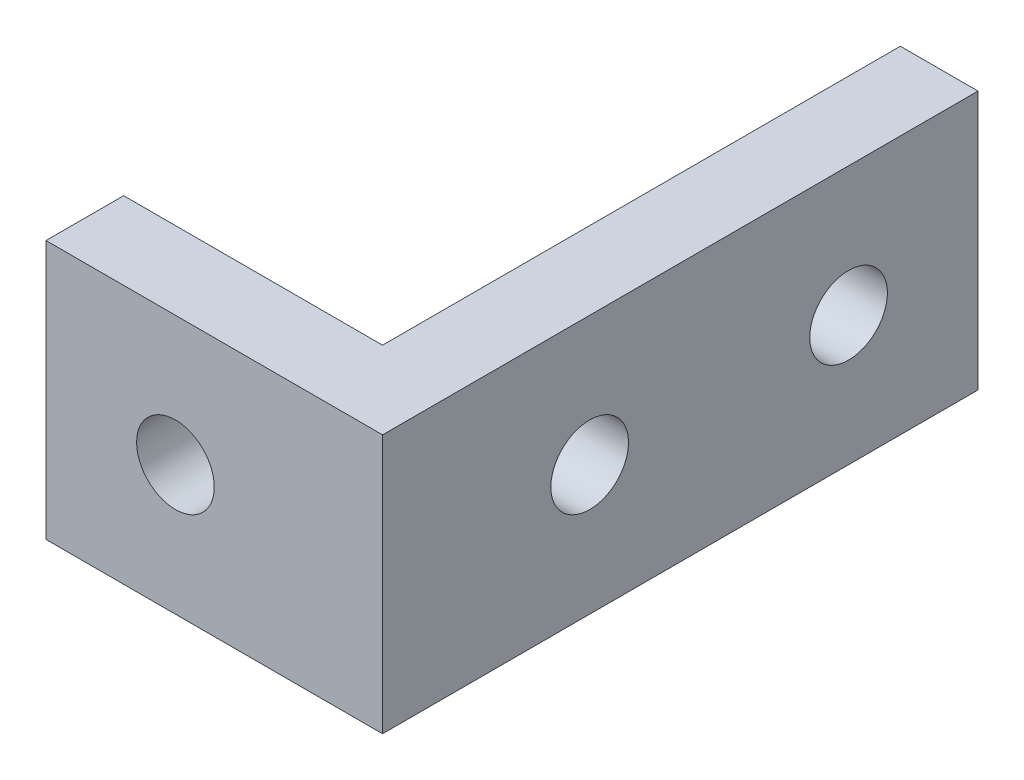
SolidWorks part; units mm, degrees
ref_plane "前视基准面" through (0, 0, 0) normal (0, 0, 1) x (1, 0, 0)
ref_plane "上视基准面" through (0, 0, 0) normal (0, 1, 0) x (1, 0, 0)
ref_plane "右视基准面" through (0, 0, 0) normal (1, 0, 0) x (0, 0, -1)
other "Configuration Table"
sketch "草图1" plane through (0, 0, 0) normal (0, 1, 0) x (1, 0, 0)
  line L0 (-13, 0) -> (0, 0)
  line L1 (0, 0) -> (0, 23)
  line L2 (0, 23) -> (-3, 23)
  line L3 (-3, 23) -> (-3, 3)
  line L4 (-3, 3) -> (-13, 3)
  line L5 (-13, 3) -> (-13, 0)
  dimension "D1" = 3
  dimension "D2" = 10
  dimension "D3" = 20
extrude "凸台-拉伸1" add sketch "草图1" along normal blind 10
sketch "草图2" plane through (-3, 0, 0) normal (-1, 0, 0) x (0, 0, 1)
  line L0 (-23, 5) -> (-3, 5) construction
  line L1 (-23, 10) -> (-23, 0) construction
  line L2 (-3, 10) -> (-3, 0) construction
  circle A0 centre (-18, 5) radius 1.5
  circle A1 centre (-8, 5) radius 1.5
  dimension "D3" = 3
  dimension "D1" = 5
  dimension "D2" = 10
extrude "切除-拉伸1" cut sketch "草图2" against normal blind 10
sketch "草图3" plane through (0, 0, -3) normal (0, 0, -1) x (-1, 0, 0)
  line L0 (3, 5) -> (13, 5) construction
  line L1 (3, 10) -> (3, 0) construction
  line L2 (13, 10) -> (13, 0) construction
  circle A0 centre (8, 5) radius 1.5
  circle A1 centre (-2, 5) radius 1.5
  dimension "D3" = 3
  dimension "D1" = 5
  dimension "D2" = 10
extrude "切除-拉伸2" cut sketch "草图3" against normal blind 10
